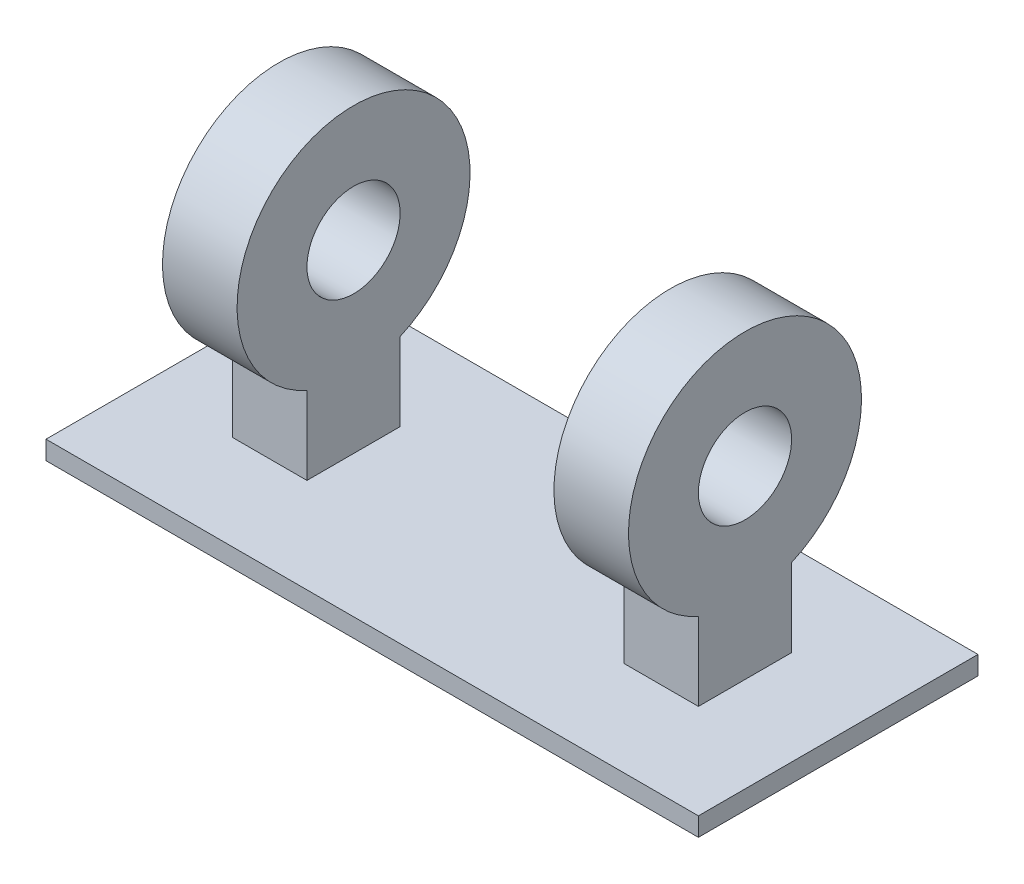
SolidWorks part; units mm, degrees
ref_plane "Front Plane" through (0, 0, 0) normal (0, 0, 1) x (1, 0, 0)
ref_plane "Top Plane" through (0, 0, 0) normal (0, 1, 0) x (1, 0, 0)
ref_plane "Right Plane" through (0, 0, 0) normal (1, 0, 0) x (0, 0, -1)
sketch "Sketch1" plane through (0, 0, 0) normal (0, 1, 0) x (1, 0, 0)
  line L1 (-35, -15) -> (35, -15)
  line L2 (-35, -15) -> (-35, 15)
  line L3 (-35, 15) -> (35, 15)
  line L4 (35, -15) -> (35, 15)
  line L5 (-35, -15) -> (35, 15) construction
  line L6 (-35, 15) -> (35, -15) construction
  point P0 (0, 0)
  dimension "D1" = 70
  dimension "D2" = 30
extrude "Boss-Extrude1" add sketch "Sketch1" along normal blind 2
ref_plane "Plane1" through (-25, 0, 0) normal (-1, 0, 0) x (0, 0, 1)
sketch "Sketch2" plane through (-25, 0, 0) normal (-1, 0, 0) x (0, 0, 1)
  line L0 (0, 7.0572) -> (0, 14.4338) construction
  line L1 (-15, 2) -> (15, 2) construction
  line L2 (-5, 10.5436) -> (-5, 7.0572)
  line L4 (5, 7.0572) -> (5, 10.5436)
  line L5 (-5, 7.0572) -> (-5, 2.1665)
  line L6 (-5, 2.1665) -> (5, 2.1665)
  line L7 (5, 2.1665) -> (5, 7.0572)
  arc A0 (5, 10.5436) -> (-5, 10.5436) centre (0, 22) ccw
  circle A1 centre (0, 22) radius 5
  dimension "D1" = 20
extrude "Boss-Extrude2" add sketch "Sketch2" against normal blind 8 separate body
ref_plane "Plane2" through (0, 0, 0) normal (-1, 0, 0) x (0, 0, 1)
mirror "Mirror3" about plane through (0, 0, 0) normal (-1, 0, 0) of bodies 102
